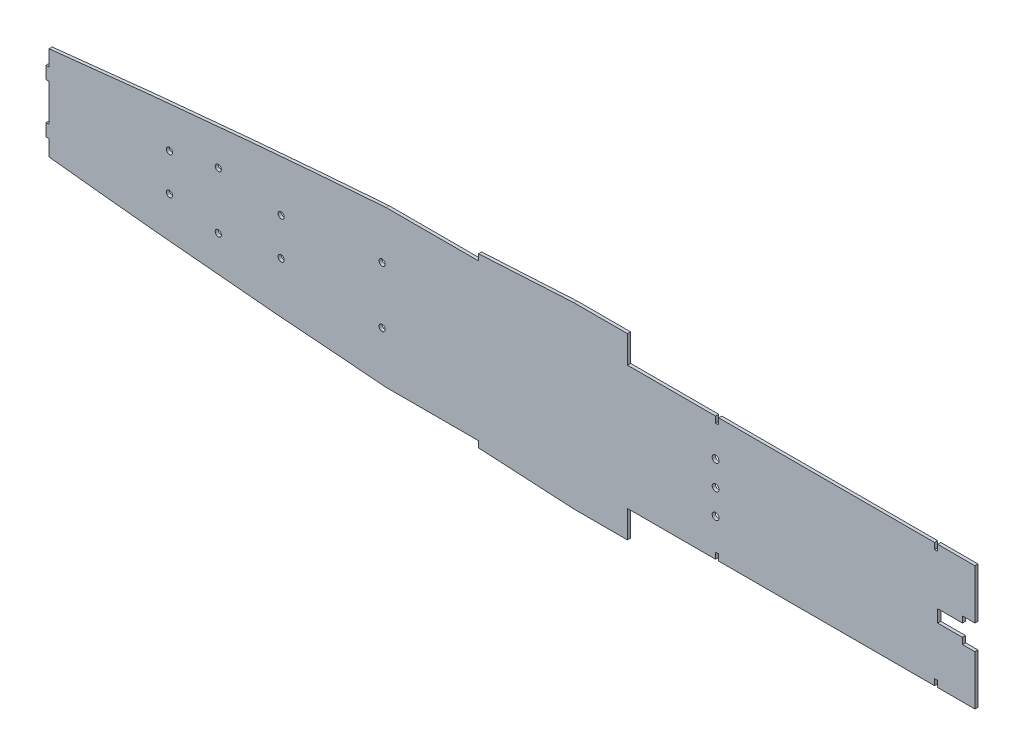
SolidWorks part; units mm, degrees
material "E-Glass Fiber"
ref_plane "Front Plane" through (0, 0, 0) normal (0, 0, 1) x (1, 0, 0)
ref_plane "Top Plane" through (0, 0, 0) normal (0, 1, 0) x (1, 0, 0)
ref_plane "Right Plane" through (0, 0, 0) normal (1, 0, 0) x (0, 0, -1)
sketch "Sketch1" plane through (0, 0, 0) normal (0, 0, 1) x (1, 0, 0)
  line L0 (0, 0) -> (508, 0) construction
  line L1 (508, 34.29) -> (508, 45.72)
  line L2 (508, 34.29) -> (635, 34.29)
  line L3 (508, 34.29) -> (508, -34.29)
  line L4 (508, -34.29) -> (635, -34.29)
  line L5 (635, 34.29) -> (635, -34.29)
  line L6 (508, 45.72) -> (383.5429, 45.72)
  line L7 (508, -45.72) -> (383.5429, -45.72)
  line L8 (508, -34.29) -> (508, -45.72)
  line L9 (161.29, 26.5379) -> (161.29, -26.5379)
  line L11 (161.29, 15.875) -> (159.7025, 15.875)
  line L12 (161.29, 15.875) -> (161.29, 9.525)
  line L13 (161.29, 9.525) -> (159.7025, 9.525)
  line L14 (159.7025, 15.875) -> (159.7025, 9.525)
  line L15 (161.29, -9.525) -> (159.7025, -9.525)
  line L16 (161.29, -9.525) -> (161.29, -15.875)
  line L17 (161.29, -15.875) -> (159.7025, -15.875)
  line L18 (159.7025, -9.525) -> (159.7025, -15.875)
  spline S0 degree 4 poles (0, 0) (0.0018, 0.005) (0.0062, 0.0145) (0.0182, 0.0319) (0.0463, 0.0632) (0.089, 0.1023) (0.1469, 0.1479) (0.229, 0.206) (0.3278, 0.2692) (0.4437, 0.3374) (0.5768, 0.4102) (0.7706, 0.5103) (1.0712, 0.6544) (1.5816, 0.8779) (2.4946, 1.2372) (4.1395, 1.8115) (7.1625, 2.7351) (12.8366, 4.2347) (22.7381, 6.4789) (39.5608, 9.7589) (62.6587, 13.6285) (90.6557, 17.7631) (121.7908, 21.8822) (152.9704, 25.646) (184.1842, 29.1144) (215.4253, 32.3259) (246.6896, 35.3031) (277.974, 38.06) (309.2766, 40.6034) (340.5957, 42.9338) (371.9303, 45.0455) (403.2798, 46.9255) (430.7232, 48.3462) (454.255, 49.3766) (473.2313, 50.0594) (486.006, 50.4329) (496.5006, 50.6673) (503.0715, 50.7648) (506.3571, 50.7959) (508, 50.8) knots 0 0 0 0 0 0.000041 0.000082 0.000164 0.000329 0.000493 0.000658 0.000951 0.001245 0.001545 0.001844 0.002657 0.003853 0.005902 0.009516 0.016281 0.028569 0.051794 0.088907 0.150314 0.211721 0.273128 0.334535 0.395942 0.457348 0.518755 0.580162 0.641569 0.702976 0.764383 0.825789 0.887196 0.9179 0.948603 0.974302 0.987151 1 1 1 1 1 construction
  spline S1 degree 4 poles (0, 0) (0.0018, 0.005) (0.0062, 0.0145) (0.0182, 0.0319) (0.0463, 0.0632) (0.089, 0.1023) (0.1469, 0.1479) (0.229, 0.206) (0.3278, 0.2692) (0.4437, 0.3374) (0.5768, 0.4102) (0.7706, 0.5103) (1.0712, 0.6544) (1.5816, 0.8779) (2.4946, 1.2372) (4.1395, 1.8115) (7.1625, 2.7351) (12.8366, 4.2347) (22.7381, 6.4789) (39.5608, 9.7589) (62.6587, 13.6285) (90.6557, 17.7631) (121.7908, 21.8822) (152.9704, 25.646) (184.1842, 29.1144) (215.4253, 32.3259) (246.6896, 35.3031) (277.974, 38.06) (309.2766, 40.6034) (340.5957, 42.9338) (371.9303, 45.0455) (403.2798, 46.9255) (430.7232, 48.3462) (454.255, 49.3766) (473.2313, 50.0594) (486.006, 50.4329) (496.5006, 50.6673) (503.0715, 50.7648) (506.3571, 50.7959) (508, 50.8) knots 0 0 0 0 0 0.000041 0.000082 0.000164 0.000329 0.000493 0.000658 0.000951 0.001245 0.001545 0.001844 0.002657 0.003853 0.005902 0.009516 0.016281 0.028569 0.051794 0.088907 0.150314 0.211721 0.273128 0.334535 0.395942 0.457348 0.518755 0.580162 0.641569 0.702976 0.764383 0.825789 0.887196 0.9179 0.948603 0.974302 0.987151 1 1 1 1 1 construction
  spline S4 degree 4 poles (0, 0) (0.0018, -0.005) (0.0062, -0.0145) (0.0182, -0.0319) (0.0463, -0.0632) (0.089, -0.1023) (0.1469, -0.1479) (0.229, -0.206) (0.3278, -0.2692) (0.4437, -0.3374) (0.5768, -0.4102) (0.7706, -0.5103) (1.0712, -0.6544) (1.5816, -0.8779) (2.4946, -1.2372) (4.1395, -1.8115) (7.1625, -2.7351) (12.8366, -4.2347) (22.7381, -6.4789) (39.5608, -9.7589) (62.6587, -13.6285) (90.6557, -17.7631) (121.7908, -21.8822) (152.9704, -25.646) (184.1842, -29.1144) (215.4253, -32.3259) (246.6896, -35.3031) (277.974, -38.06) (309.2766, -40.6034) (340.5957, -42.9338) (371.9303, -45.0455) (403.2798, -46.9255) (430.7232, -48.3462) (454.255, -49.3766) (473.2313, -50.0594) (486.006, -50.4329) (496.5006, -50.6673) (503.0715, -50.7648) (506.3571, -50.7959) (508, -50.8) knots 0 0 0 0 0 0.000041 0.000082 0.000164 0.000329 0.000493 0.000658 0.000951 0.001245 0.001545 0.001844 0.002657 0.003853 0.005902 0.009516 0.016281 0.028569 0.051794 0.088907 0.150314 0.211721 0.273128 0.334535 0.395942 0.457348 0.518755 0.580162 0.641569 0.702976 0.764383 0.825789 0.887196 0.9179 0.948603 0.974302 0.987151 1 1 1 1 1 construction
  spline S7 degree 1 poles (6.9536, 0) (508.0063, -48.26) knots 0 0 1 1 construction
  spline S8 degree 1 poles (6.9536, 0) (508.0063, 48.26) knots 0 0 1 1 construction
  spline S9 degree 3 poles (508.0063, -48.26) (505.389, -48.2535) (500.1595, -48.1854) (489.6619, -47.9832) (471.2967, -47.4768) (445.0522, -46.4694) (413.5702, -44.9339) (371.608, -42.5248) (319.1882, -38.9156) (256.3481, -33.728) (204.0482, -28.6792) (162.2644, -24.1404) (130.9623, -20.4508) (99.7076, -16.4227) (73.7194, -12.7048) (52.9887, -9.4159) (37.4884, -6.7357) (24.6309, -4.2526) (15.7185, -2.2776) (10.6685, -1.0328) (8.1898, -0.3612) (6.9536, 0) knots 0.013175 0.013175 0.013175 0.013175 0.028594 0.044013 0.074852 0.136528 0.198205 0.259881 0.383235 0.506588 0.629941 0.691617 0.753294 0.81497 0.876647 0.907485 0.938323 0.969162 0.984581 0.99229 1 1 1 1
  spline S10 degree 3 poles (6.9536, 0) (8.1898, 0.3612) (10.6685, 1.0328) (15.7185, 2.2776) (24.6309, 4.2526) (37.4884, 6.7357) (52.9887, 9.4159) (73.7194, 12.7048) (99.7076, 16.4227) (130.9623, 20.4508) (162.2644, 24.1404) (204.0482, 28.6792) (256.3481, 33.728) (319.1882, 38.9156) (371.608, 42.5248) (413.5702, 44.9339) (445.0522, 46.4694) (471.2967, 47.4768) (489.6619, 47.9832) (500.1595, 48.1854) (505.389, 48.2535) (508.0063, 48.26) knots 0.013175 0.013175 0.013175 0.013175 0.020885 0.028594 0.044013 0.074852 0.10569 0.136528 0.198205 0.259881 0.321558 0.383235 0.506588 0.629941 0.753294 0.81497 0.876647 0.938323 0.969162 0.984581 1 1 1 1
  dimension "D1" = 508
  dimension "D2" = 68.58
  dimension "D3" = 45.72
  dimension "D4" = 127
  dimension "D5" = 473.71
  dimension "D7" = 1.5875
  dimension "D8" = 6.35
  dimension "D9" = 19.05
  dimension "D6" = 2.54
extrude "Boss-Extrude1" add sketch "Sketch1" along normal blind 1.5875
sketch "Sketch2" plane through (635, 0, 0) normal (1, 0, 0) x (0, 0, -1)
  line L0 (-0.7938, 34.29) -> (-0.7937, -34.29) construction
  line L3 (-1.5875, 34.29) -> (0, 34.29) construction
  line L6 (-1.5875, -34.29) -> (0, -34.29) construction
  line L7 (0, 0) -> (-1.5875, 0) construction
  line L8 (0, 34.29) -> (0, -34.29) construction
  line L9 (-1.5875, 34.29) -> (-1.5875, -34.29) construction
sketch "Sketch3" plane through (0, 0, 1.5875) normal (0, 0, 1) x (1, 0, 0)
  line L0 (508, 45.72) -> (429.9476, 45.72) construction
  line L1 (508, 34.29) -> (457.2, 34.29)
  line L2 (508, 34.29) -> (508, 45.72)
  line L3 (508, 45.72) -> (457.2, 45.72)
  line L4 (457.2, 34.29) -> (457.2, 45.72)
  line L5 (508, -45.72) -> (429.9476, -45.72) construction
  line L6 (508, -34.29) -> (457.2, -34.29)
  line L7 (508, -34.29) -> (508, -45.72)
  line L8 (508, -45.72) -> (457.2, -45.72)
  line L9 (457.2, -34.29) -> (457.2, -45.72)
  line L10 (635, 34.29) -> (635, -34.29) construction
  line L11 (628.65, 3.175) -> (615.95, 3.175)
  line L12 (161.29, 9.525) -> (161.29, -9.525) construction
  line L13 (628.65, -3.175) -> (615.95, -3.175)
  line L14 (615.95, 3.175) -> (615.95, -3.175)
  line L15 (161.29, 0) -> (635, 0) construction
  line L17 (628.65, -3.175) -> (628.65, -6.35)
  line L18 (628.65, 6.35) -> (635, 6.35)
  line L19 (628.65, 6.35) -> (628.65, 3.175)
  line L20 (628.65, -6.35) -> (635, -6.35)
  line L21 (635, 6.35) -> (635, -6.35)
  line L22 (635, 34.29) -> (457.2, 34.29)
  line L23 (635, 34.29) -> (635, 31.75)
  line L24 (635, 31.75) -> (457.2, 31.75)
  line L25 (457.2, 34.29) -> (457.2, 31.75)
  line L26 (635, -34.29) -> (457.2, -34.29)
  line L27 (635, -34.29) -> (635, -31.75)
  line L28 (635, -31.75) -> (457.2, -31.75)
  line L29 (457.2, -34.29) -> (457.2, -31.75)
  line M4 (429.9476, -45.72) -> (508, -45.72)
  line M5 (508, -45.72) -> (508, -34.29)
  line M6 (508, -34.29) -> (635, -34.29)
  line M7 (635, -34.29) -> (635, 34.29)
  line M8 (635, 34.29) -> (508, 34.29)
  line M9 (508, 34.29) -> (508, 45.72)
  line M10 (508, 45.72) -> (429.9476, 45.72)
  dimension "D1" = 50.8
  dimension "D2" = 6.35
  dimension "D3" = 19.05
  dimension "D4" = 12.7
  dimension "D5" = 6.35
  dimension "D6" = 2.54
extrude "Cut-Extrude1" cut sketch "Sketch3" against normal through all contours L6 L9 M4 M5 | L4 L1 M9 M10 | L25 L24 M8 M7 | L29 L28 M6 M7 | L15 L14 L13 L17 L20 M7 | L14 L15 L21 L18 L19 L11
sketch "Sketch4" plane through (0, 0, 1.5875) normal (0, 0, 1) x (1, 0, 0)
  line L0 (635, -31.75) -> (457.2, -31.75) construction
  line L1 (615.95, 3.175) -> (615.95, -3.175) construction
  line L2 (503.9042, 28.575) -> (502.3167, 28.575)
  line L3 (502.3167, 31.75) -> (502.3167, 28.575)
  line L4 (503.9042, 31.75) -> (503.9042, 28.575)
  line L5 (635, 31.75) -> (457.2, 31.75) construction
  line L6 (615.95, 31.75) -> (614.3625, 31.75)
  line L7 (615.95, 31.75) -> (615.95, 28.575)
  line L8 (615.95, 28.575) -> (614.3625, 28.575)
  line L9 (614.3625, 31.75) -> (614.3625, 28.575)
  line L11 (503.9042, 31.75) -> (502.3167, 31.75)
  line L12 (503.9042, -31.75) -> (502.3167, -31.75)
  line L13 (502.3167, -28.575) -> (502.3167, -31.75)
  line L14 (503.9042, -28.575) -> (503.9042, -31.75)
  line L15 (503.9042, -28.575) -> (502.3167, -28.575)
  line L16 (615.95, -31.75) -> (614.3625, -31.75)
  line L17 (614.3625, -28.575) -> (614.3625, -31.75)
  line L18 (615.95, -28.575) -> (615.95, -31.75)
  line L19 (615.95, -28.575) -> (614.3625, -28.575)
  dimension "D1" = 3.175
  dimension "D2" = 1.5875
  dimension "D5" = 112.0457
  dimension "D3" = 2
  dimension "D4" = 2
extrude "Cut-Extrude2" cut sketch "Sketch4" against normal through all
sketch "Sketch6" plane through (0, 0, 1.5875) normal (0, 0, 1) x (1, 0, 0)
  line L0 (381, 43.0197) -> (381, -43.0197) construction
  line L1 (635, 31.75) -> (635, 6.35) construction
  line L2 (333.6619, 39.8447) -> (381, 39.8447)
  line L3 (381, 39.8447) -> (381, 43.0197)
  line L4 (161.29, 0) -> (615.95, 0) construction
  line L6 (615.95, 3.175) -> (615.95, -3.175) construction
  line L7 (381, 43.0197) -> (333.6619, 43.0197)
  line L8 (333.6619, 43.0197) -> (333.6619, 39.8447)
  line L9 (333.6619, -43.0197) -> (333.6619, -39.8447)
  line L10 (381, -43.0197) -> (333.6619, -43.0197)
  line L11 (381, -39.8447) -> (381, -43.0197)
  line L12 (333.6619, -39.8447) -> (381, -39.8447)
  line L13 (161.29, 9.525) -> (161.29, -9.525) construction
  spline S0 degree 3 poles (161.29, 23.9816) (161.6168, 24.0187) (172.3834, 25.2396) (204.0482, 28.6792) (256.3481, 33.728) (319.1882, 38.9156) (371.608, 42.5248) (408.5368, 44.6449) (424.4886, 45.456) (429.9476, 45.72) knots 0.319627 0.319627 0.319627 0.319627 0.321558 0.383235 0.506588 0.629941 0.753294 0.81497 0.847055 0.847055 0.847055 0.847055 construction
  spline S1 degree 3 poles (429.9476, -45.72) (424.4886, -45.456) (408.5368, -44.6449) (371.608, -42.5248) (319.1882, -38.9156) (256.3481, -33.728) (204.0482, -28.6792) (172.3834, -25.2396) (161.6168, -24.0187) (161.29, -23.9816) knots 0.166121 0.166121 0.166121 0.166121 0.198205 0.259881 0.383235 0.506588 0.629941 0.691617 0.693548 0.693548 0.693548 0.693548 construction
  dimension "D1" = 254
  dimension "D2" = 3.175
extrude "Cut-Extrude3" cut sketch "Sketch6" against normal through all
sketch "Sketch7" plane through (0, 0, 1.5875) normal (0, 0, 1) x (1, 0, 0)
  line L1 (615.95, 0) -> (575.4012, 0) construction
  line L2 (615.95, 3.175) -> (615.95, -3.175) construction
  circle A0 centre (331.6888, 14.478) radius 1.5875
  circle A1 centre (331.6888, -14.478) radius 1.5875
  circle A2 centre (247.8688, 14.478) radius 1.5875
  circle A3 centre (247.8688, -14.478) radius 1.5875
  dimension "D1" = 3.175
  dimension "D3" = 83.82
  dimension "D2" = 28.956
extrude "ARTS4 mount" cut sketch "Sketch7" against normal through all
sketch "Sketch8" plane through (0, 0, 1.5875) normal (0, 0, 1) x (1, 0, 0)
  line L0 (615.95, 0) -> (598.1663, 0) construction
  line L1 (615.95, 3.175) -> (615.95, -3.175) construction
  circle A0 centre (280.0184, 9.525) radius 1.5875
  circle A1 centre (280.0184, -9.525) radius 1.5875
  circle A2 centre (222.8938, -9.525) radius 1.5875
  circle A3 centre (222.8938, 9.525) radius 1.5875
  dimension "D3" = 3.175
  dimension "D1" = 19.05
  dimension "D2" = 57.1246
extrude "Telemetrum Mount" cut sketch "Sketch8" against normal through all
sketch "Sketch9" plane through (0, 0, 1.5875) normal (0, 0, 1) x (1, 0, 0)
  line L0 (615.95, 0) -> (407.9934, 0) construction
  line L1 (615.95, 3.175) -> (615.95, -3.175) construction
  circle A0 centre (502.3167, -12.7) radius 1.7462
  circle A1 centre (502.3167, 12.7) radius 1.7462
  circle A2 centre (502.3167, 0) radius 1.7462
  dimension "D1" = 3.4925
  dimension "D2" = 12.7
extrude "Cut-Extrude4" cut sketch "Sketch9" against normal through all
